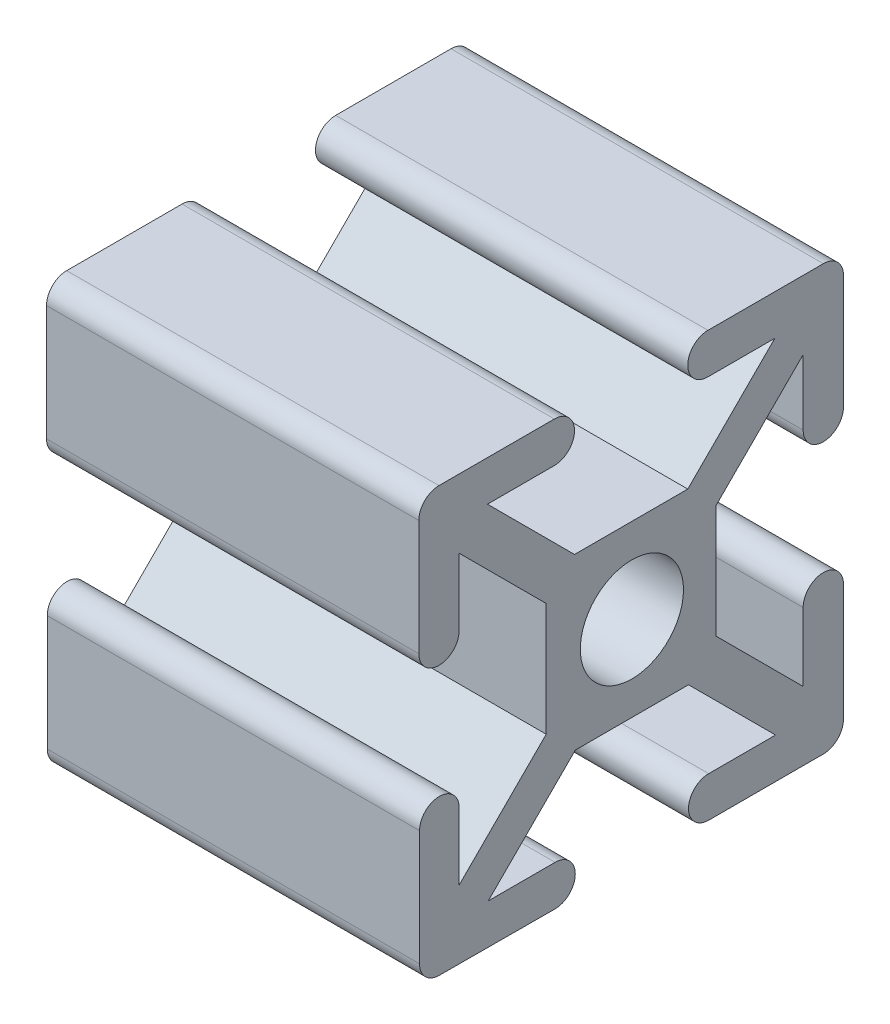
SolidWorks part; units mm, degrees
ref_plane "Alzado" through (0, 0, 0) normal (0, 0, 1) x (1, 0, 0)
ref_plane "Planta" through (0, 0, 0) normal (0, 1, 0) x (1, 0, 0)
ref_plane "Vista lateral" through (0, 0, 0) normal (1, 0, 0) x (0, 0, -1)
sketch "Croquis1" plane through (0, 0, 0) normal (1, 0, 0) x (0, 0, -1)
  line L0 (-33.2938, -24.6819) -> (-33.2938, -23.2569) construction
  line L1 (-14.241, -40.8319) -> (-9.516, -40.8319)
  line L2 (-34.7188, -15.107) -> (-34.7188, -23.2569)
  line L3 (-33.2938, -13.682) -> (-25.1438, -13.682)
  line L4 (-14.2938, -13.682) -> (-6.1438, -13.682)
  line L5 (-29.816, -40.8319) -> (-25.091, -40.8319)
  line L6 (-25.7188, -24.6819) -> (-25.7188, -32.6819)
  line L7 (-34.666, -34.1069) -> (-34.666, -42.2569)
  line L8 (-33.2674, -43.6555) -> (-25.091, -43.6819)
  line L9 (-4.7188, -15.107) -> (-4.7188, -23.1532)
  line L10 (-31.8688, -18.5319) -> (-31.8688, -23.2569)
  line L11 (-4.7188, -34.0032) -> (-4.7188, -42.2569)
  line L12 (-23.7188, -15.107) -> (-25.1438, -15.107) construction
  line L13 (-14.241, -43.6819) -> (-6.1438, -43.6819)
  line L14 (-29.8688, -16.532) -> (-25.1438, -16.532)
  line L15 (-31.8688, -34.1069) -> (-31.8688, -38.8319)
  line L16 (-15.7188, -15.107) -> (-14.2938, -15.107) construction
  line L17 (-14.2938, -16.532) -> (-9.5688, -16.532)
  line L18 (-6.1438, -24.5782) -> (-6.1438, -23.1532) construction
  line L19 (-23.7188, -22.682) -> (-29.8688, -16.532)
  line L20 (-7.5688, -18.532) -> (-7.5688, -23.1532)
  line L21 (-6.1438, -32.5782) -> (-6.1438, -34.0032) construction
  line L22 (-25.7188, -24.6819) -> (-31.8688, -18.5319)
  line L23 (-7.5688, -34.0032) -> (-7.5688, -38.832)
  line L24 (-15.666, -42.2569) -> (-14.241, -42.2569) construction
  line L25 (-25.7188, -32.6819) -> (-31.8688, -38.8319)
  line L26 (-23.7188, -22.682) -> (-15.7188, -22.682)
  line L27 (-15.7188, -22.682) -> (-9.5688, -16.532)
  line L28 (-33.2674, -32.6819) -> (-33.2674, -34.1069) construction
  line L29 (-29.816, -40.8319) -> (-23.666, -34.6819)
  line L30 (-23.666, -34.6819) -> (-15.666, -34.6819)
  line L31 (-15.666, -34.6819) -> (-9.516, -40.8319)
  line L32 (-23.666, -42.2569) -> (-25.091, -42.2569) construction
  line L33 (-13.7188, -32.682) -> (-7.5688, -38.832)
  line L34 (-13.7188, -24.682) -> (-7.5688, -18.532)
  line L35 (-13.7188, -24.682) -> (-13.7188, -32.682)
  circle A0 centre (-19.666, -28.6819) radius 3.645
  arc A1 (-34.7188, -23.2569) -> (-31.8688, -23.2569) centre (-33.2938, -23.2569) ccw
  arc A2 (-25.1438, -16.532) -> (-25.1438, -13.682) centre (-25.1438, -15.107) ccw
  arc A3 (-14.2938, -13.682) -> (-14.2938, -16.532) centre (-14.2938, -15.107) ccw
  arc A4 (-7.5688, -23.1532) -> (-4.7188, -23.1532) centre (-6.1438, -23.1532) ccw
  arc A5 (-4.7188, -34.0032) -> (-7.5688, -34.0032) centre (-6.1438, -34.0032) ccw
  arc A6 (-14.241, -40.8319) -> (-14.241, -43.6819) centre (-14.241, -42.2569) ccw
  arc A7 (-31.8688, -34.1069) -> (-34.666, -34.1069) centre (-33.2674, -34.1069) ccw
  arc A8 (-25.091, -43.6819) -> (-25.091, -40.8319) centre (-25.091, -42.2569) ccw
  arc A9 (-34.666, -42.2569) -> (-33.2674, -43.6555) centre (-33.2674, -42.2569) ccw
  arc A10 (-6.1438, -43.6819) -> (-4.7188, -42.2569) centre (-6.1438, -42.2569) ccw
  arc A11 (-4.7188, -15.107) -> (-6.1438, -13.682) centre (-6.1438, -15.107) ccw
  arc A12 (-33.2938, -13.682) -> (-34.7188, -15.107) centre (-33.2938, -15.107) ccw
  dimension "D1" = 1.425
  dimension "D2" = 1.425
  dimension "D3" = 1.425
  dimension "D4" = 1.425
  dimension "D5" = 1.425
  dimension "D6" = 1.425
  dimension "D7" = 1.425
extrude "Saliente-Extruir1" add sketch "Croquis1" along normal blind 26.3
